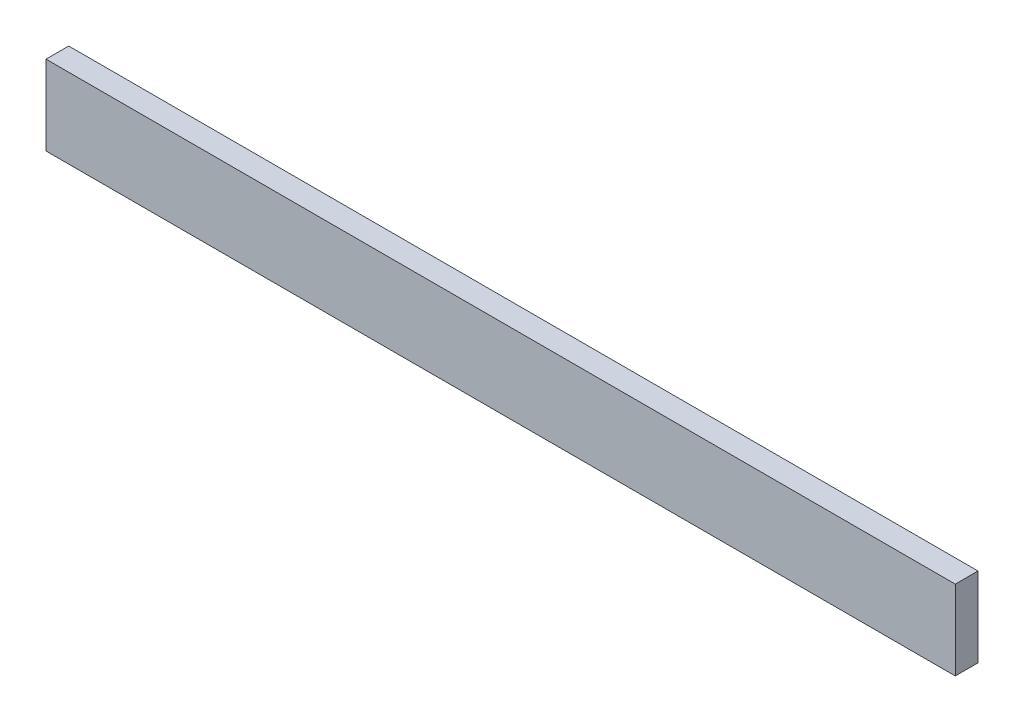
SolidWorks part; units mm, degrees
ref_plane "Front Plane" through (0, 0, 0) normal (0, 0, 1) x (1, 0, 0)
ref_plane "Top Plane" through (0, 0, 0) normal (0, 1, 0) x (1, 0, 0)
ref_plane "Right Plane" through (0, 0, 0) normal (1, 0, 0) x (0, 0, -1)
sketch "Sketch1" plane through (0, 0, 0) normal (0, 0, 1) x (1, 0, 0)
  line L1 (40, -3.5) -> (-40, -3.5)
  line L2 (40, -3.5) -> (40, 3.5)
  line L3 (40, 3.5) -> (-40, 3.5)
  line L4 (-40, -3.5) -> (-40, 3.5)
  line L5 (40, -3.5) -> (-40, 3.5) construction
  line L6 (40, 3.5) -> (-40, -3.5) construction
  point P0 (0, 0)
  dimension "D1" = 7
  dimension "D2" = 80
extrude "Boss-Extrude1" add sketch "Sketch1" along normal blind 2
